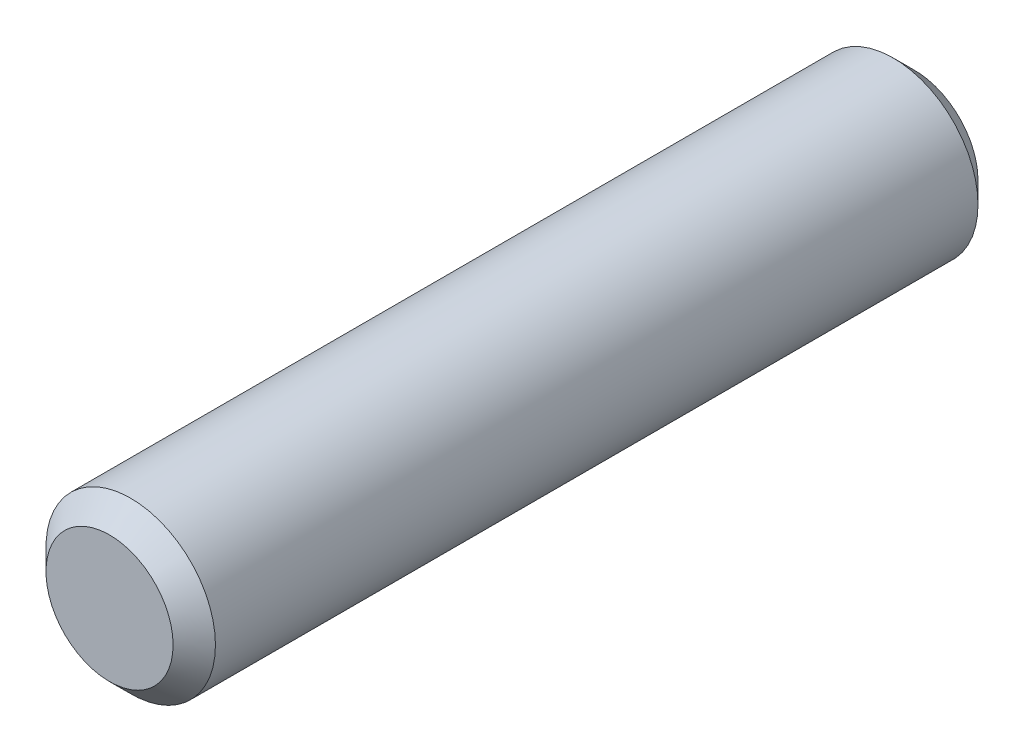
SolidWorks part; units mm, degrees
material "AISI 304"
ref_plane "Front Plane" through (0, 0, 0) normal (0, 0, 1) x (1, 0, 0)
ref_plane "Top Plane" through (0, 0, 0) normal (0, 1, 0) x (1, 0, 0)
ref_plane "Right Plane" through (0, 0, 0) normal (1, 0, 0) x (0, 0, -1)
sketch "Sketch1" plane through (0, 0, 0) normal (0, 0, 1) x (1, 0, 0)
  circle A0 centre (0, 0) radius 2
  dimension "D1" = 4
extrude "Boss-Extrude1" add sketch "Sketch1" along normal blind 19
chamfer "Chamfer1" distance 0.5 angle 45 2 edges at (2, 0, 0) (2, 0, 19)
